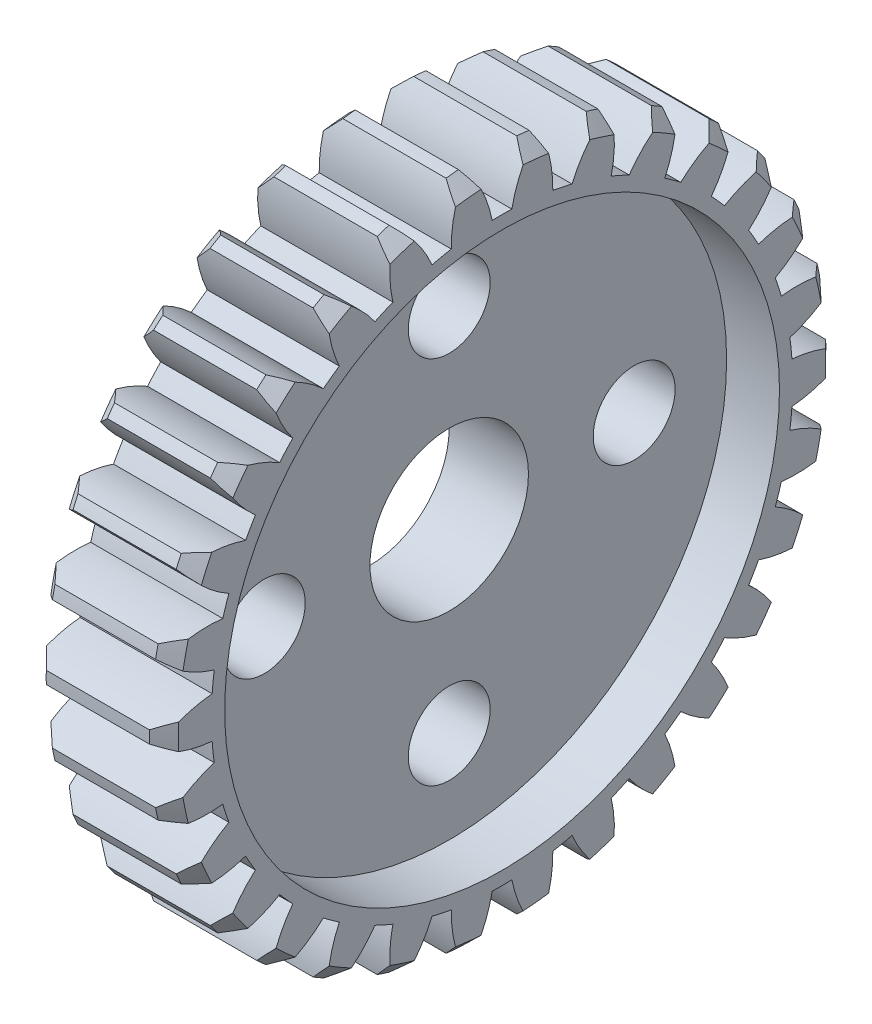
SolidWorks part; units mm, degrees
ref_plane "Plane1" through (0, 0, 0) normal (0, 0, 1) x (1, 0, 0)
ref_plane "Plane2" through (0, 0, 0) normal (0, 1, 0) x (1, 0, 0)
ref_plane "Plane3" through (0, 0, 0) normal (1, 0, 0) x (0, 0, -1)
sketch "HoldingSke" plane through (0, 0, 0) normal (0, 1, 0) x (1, 0, 0)
  line L0 (0, 0) -> (1.0825, -0.625)
  line L1 (-15, 0) -> (100, 0) construction
  line L2 (0, 0) -> (-2.1039, 2.3779)
  line L3 (0, 0) -> (-11.863, 4.5341)
  line L4 (0, 0) -> (7.479, 4.318)
  line L5 (0, 0) -> (-46.8476, -17.4728)
  line L6 (0, 0) -> (-4.1448, -2.7965)
  line L7 (-2.1039, 2.3779) -> (8.6586, 51.2059)
  line L8 (-76.2, 54.61) -> (-75.2, 54.61)
  line L9 (-71.009, 38.7566) -> (-53.1078, 45.2721)
  line L10 (-76.2, 71.12) -> (104.1128, 71.12)
  line L11 (0, 0) -> (-5, 0)
  line L12 (-76.2, 101.6) -> (-76.17, 101.6)
  line L13 (24.9733, 27.94) -> (52.9518, 28.4284)
  line L14 (24.9733, 27.94) -> (24.9743, 27.94)
  line L15 (24.9733, 27.94) -> (100.4006, 29.5858)
  line L16 (-63.627, -0.8) -> (-12.827, -0.8)
  circle A0 centre (0, 0) radius 3
  circle A1 centre (0, 0) radius 10.999
  circle A2 centre (0, 0) radius 37.5
  circle A3 centre (0, 0) radius 3
  dimension "MHD" = 21.998
  dimension "Hub_dia" = 75
  dimension "Bore" = 6
  dimension "MBD" = 6
  dimension "Num_teeth" = 30
  dimension "Pitch" = 1.25
  dimension "Overall_len" = 50
  dimension "Show_teeth" = 30
  dimension "Thickness" = 5
  dimension "OAL" = 50.0001
  dimension "T_dim" = 1
  dimension "Ap" = 20
  dimension "H" = 19.05
  dimension "Pitch_radius" = 180.3128
  dimension "Width" = 5
  dimension "Backlash" = 0.03
  dimension "Addendum_fac" = 1
  dimension "Dedendum_fac" = 1.25
  dimension "Clearance_fac" = 0.25
  dimension "Dedendum_add" = 0.001
  dimension "Module" = 0.8
sketch "BasProSke" plane through (0, 0, 0) normal (0, 1, 0) x (1, 0, 0)
  line L0 (-10, 0) -> (60, 0) construction
  line L1 (0, 0) -> (0, 12.8)
  line L2 (0, 0) -> (5, 0)
  line L3 (5, 0) -> (5, 12.8)
  line L4 (5, 12.8) -> (0, 12.8)
  dimension "Thickness" = 5
  dimension "Diameter" = 25.6
revolve "Base-Revolve" add sketch "BasProSke" angle 360 about L0
sketch "TooCutSke" plane through (0, 0, 0) normal (1, 0, 0) x (0, 0, -1)
  line L1 (0, 0) -> (0, 107) construction
  line L2 (0, 0) -> (-0.6805, 11.9807) construction
  line L3 (0, 0) -> (-2.5058, 23.8411) construction
  line L4 (-0.6805, 11.9807) -> (-1.2529, 11.9205) construction
  arc A0 (0.3724, 10.9927) -> (-0.3724, 10.9927) centre (0, 0) ccw
  arc A1 (1.1205, 12.7764) -> (-1.1205, 12.7764) centre (0, 0) ccw
  circle A2 centre (0, 0) radius 12 construction
  circle A3 centre (0, 0) radius 11.2763 construction
  arc A4 (-0.3724, 10.9927) -> (-1.1205, 12.7764) centre (-5.0822, 10.0661) ccw
  arc A5 (1.1205, 12.7764) -> (0.3724, 10.9927) centre (5.0822, 10.0661) ccw
  dimension "Root_dia" = 21.998
  dimension "Overcut_dia" = 25.6508
  dimension "Pitch_dia" = 24
  dimension "Base_dia" = 22.5526
  dimension "Flank_rad" = 4.8
  dimension "Half_ang" = 6
  dimension "Half_CT" = 0.5755
extrude "ToothCut" cut sketch "TooCutSke" along normal through all
fillet "Breaks" [suppressed] radius 0.016
fillet "RootFillets" [suppressed] radius 0.201
pattern_circular "TeethCuts" count 30 every 12 about axis through (-10, 0, 0) along (1, 0, 0) of "ToothCut", "RootFillets", "Breaks"
sketch "HubNeaOneSke" plane through (0, 0, 0) normal (-1, 0, 0) x (0, 0, 1)
  circle A0 centre (0, 0) radius 10.999
  dimension "Diameter" = 21.998
extrude "HubNearOne" [suppressed] add sketch "HubNeaOneSke" along normal blind 45.0001
sketch "HubNeaBotSke" plane through (0, 0, 0) normal (-1, 0, 0) x (0, 0, 1)
  circle A0 centre (0, 0) radius 10.999
  dimension "Diameter" = 21.998
extrude "HubNearBoth" [suppressed] add sketch "HubNeaBotSke" along normal blind 22.5
ref_plane "FarPln" through (5, 0, 0) normal (1, 0, 0) x (0, 0, -1)
sketch "HubFarSke" plane through (5, 0, 0) normal (1, 0, 0) x (0, 0, -1)
  circle A0 centre (0, 0) radius 10.999
  dimension "Diameter" = 21.998
extrude "HubFar" [suppressed] add sketch "HubFarSke" along normal blind 22.5
sketch "BorSke" plane through (0, 0, 0) normal (1, 0, 0) x (0, 0, -1)
  circle A0 centre (0, 0) radius 3
  dimension "Diameter" = 6
extrude "Bore" cut sketch "BorSke" along normal mid plane 100.0001
sketch "KeySke" plane through (0, 0, 0) normal (1, 0, 0) x (0, 0, -1)
  line L0 (-1, 0) -> (-1, 4)
  line L1 (-1, 4) -> (1, 4)
  line L2 (1, 4) -> (1, 0)
  line L3 (0, 0) -> (0, 34) construction
  line L4 (-1, 0) -> (1, 0)
  dimension "Offset" = 4
  dimension "Width" = 2
extrude "Keyway" [suppressed] cut sketch "KeySke" along normal mid plane 100.0001
pattern_circular "Keyway2" [suppressed] count 2 every 90 about axis through (-10, 0, 0) along (1, 0, 0)
sketch "草图1" plane through (5, 0, 0) normal (1, 0, 0) x (0, 0, -1)
  circle A0 centre (0, 0) radius 10.5
  dimension "D1" = 21
extrude "切除-拉伸1" cut sketch "草图1" against normal blind 2
sketch "草图2" plane through (3, 0, 0) normal (1, 0, 0) x (0, 0, -1)
  circle A0 centre (0, 0) radius 7 construction
  circle A1 centre (0, 7) radius 1.55
  circle A2 centre (7, 0) radius 1.55
  circle A3 centre (0, -7) radius 1.55
  circle A4 centre (-7, 0) radius 1.55
  point P14 (0, 0)
  dimension "D1" = 3.1
  dimension "D3" = 14
  dimension "D2" = 4
extrude "切除-拉伸2" cut sketch "草图2" against normal blind 5
sketch "草图3" plane through (0, 0, 0) normal (0, 0, 1) x (1, 0, 0)
  line L0 (0, 15.3483) -> (0, 12.2523)
  line L1 (0, 12.2523) -> (3.096, 15.3483)
  line L9 (3.096, 15.3483) -> (0, 15.3483)
  line L10 (0, 12.7032) -> (0, 10.8299) construction
  line L11 (0, 12.7523) -> (5, 12.7523) construction
  dimension "D1" = 45
  dimension "D2" = 0.5
sketch "草图4" plane through (0, 0, 0) normal (-1, 0, 0) x (0, 0, 1)
  circle A0 centre (0, 0) radius 12.2523
sweep "切除-扫描1" cut profiles "草图3" path "草图4"
ref_plane "基准面1" through (2.5, 0, 0) normal (-1, 0, 0) x (0, 0, 1)
mirror "镜向1" about plane through (2.5, 0, 0) normal (-1, 0, 0) of "切除-扫描1"
equation "' \"Module@HoldingSke\" = 6.35"
equation "' \"Num_teeth@HoldingSke\" = 12"
equation "' \"Ap@HoldingSke\" =  20"
equation "' \"Ap@HoldingSke\" = 20"
equation "' \"Width@HoldingSke\" = 0.5 * 25.4"
equation "' \"Hub_dia@HoldingSke\"= 1 * 25.4"
equation "' \"Hub_dia@HoldingSke\" = 1 * 25.4"
equation "' \"Overall_len@HoldingSke\" = 1.0 * 25.4"
equation "' \"Bore@HoldingSke\" = 0.75 * 25.4"
equation "' \"T_dim@HoldingSke\" = 0.1 * 25.4"
equation "' \"Width@KeySke\" = 0.25 * 25.4"
equation "' \"Show_teeth@HoldingSke\" = 13"
equation "' \"Backlash@HoldingSke\" = 0.009 * 25.4"
equation "' \"Addendum_fac@HoldingSke\" = 1.0"
equation "' \"Dedendum_fac@HoldingSke\" = 1.25"
equation "' \"Dedendum_add@HoldingSke\" = 0.00005 * 25.4"
equation "' \"Clearance_fac@HoldingSke\" = 0.25"
equation "\"Pitch@HoldingSke\" = 1 / \"Module@HoldingSke\""
equation "\"Overcut_dia@TooCutSke\" = (\"Num_teeth@HoldingSke\" + 2 * \"Addendum_fac@HoldingSke\") / \"Pitch@HoldingSke\" + 0.002 * 25.4"
equation "\"Pitch_dia@TooCutSke\" = \"Num_teeth@HoldingSke\" / \"Pitch@HoldingSke\""
equation "\"Base_dia@TooCutSke\" = \"Num_teeth@HoldingSke\" / \"Pitch@HoldingSke\" * cos((\"Ap@HoldingSke\"  * 3.14159265 / 180))"
equation "\"Root_dia@TooCutSke\" = (\"Num_teeth@HoldingSke\" + 2) / \"Pitch@HoldingSke\" - 2 * (\"Addendum_fac@HoldingSke\" + \"Dedendum_fac@HoldingSke\") / \"Pitch@HoldingSke\" - \"Dedendum_add@HoldingSke\" * 2"
equation "\"Half_ang@TooCutSke\" = 180 / \"Num_teeth@HoldingSke\""
equation "\"Half_CT@TooCutSke\" = \"Num_teeth@HoldingSke\" / \"Pitch@HoldingSke\" * sin((3.14159265 / 2 / \"Num_teeth@HoldingSke\")) / 2 - 7 * \"Backlash@HoldingSke\" / 4"
equation "\"Flank_rad@TooCutSke\" = \"Num_teeth@HoldingSke\" / \"Pitch@HoldingSke\" / 5"
equation "\"Radius@RootFillets\" = \"Clearance_fac@HoldingSke\" / \"Pitch@HoldingSke\" + \"Dedendum_add@HoldingSke\""
equation "\"Break_rad@Breaks\" = 0.02 / \"Pitch@HoldingSke\""
equation "\"Thickness@HoldingSke\" = \"Width@HoldingSke\""
equation "\"OAL@HoldingSke\" = \"Thickness@HoldingSke\""
equation "\"MHD@HoldingSke\" = (\"Num_teeth@HoldingSke\" + 2) / \"Pitch@HoldingSke\" - 2 * (\"Addendum_fac@HoldingSke\" + \"Dedendum_fac@HoldingSke\")  / \"Pitch@HoldingSke\" - \"Dedendum_add@HoldingSke\" * 2"
equation "\"MBD@HoldingSke\" = (\"Num_teeth@HoldingSke\" + 2) / \"Pitch@HoldingSke\" - 2 * (\"Addendum_fac@HoldingSke\" + \"Dedendum_fac@HoldingSke\")  / \"Pitch@HoldingSke\" - \"Dedendum_add@HoldingSke\" * 2 - 0.002 * 25.4"
equation "\"MHD@HoldingSke\" = ((sgn( \"MHD@HoldingSke\" - \"Hub_dia@HoldingSke\" )-1)*( \"MHD@HoldingSke\" - \"Hub_dia@HoldingSke\" ))/-2+ \"Hub_dia@HoldingSke\""
equation "\"MBD@HoldingSke\" = ((sgn( \"MBD@HoldingSke\" - \"Bore@HoldingSke\" )-1)*( \"MBD@HoldingSke\" - \"Bore@HoldingSke\" ))/-2+ \"Bore@HoldingSke\""
equation "\"OAL@HoldingSke\" = ((sgn( \"OAL@HoldingSke\" - \"Overall_len@HoldingSke\" )+1)*( \"OAL@HoldingSke\" - \"Overall_len@HoldingSke\" ))/2 + \"Overall_len@HoldingSke\" + 0.000002 * 25.4"
equation "\"Num_teeth@TeethCuts\" = int( \"Show_teeth@HoldingSke\" ) + 1"
equation "\"Num_teeth@TeethCuts\" = ((sgn( \"Num_teeth@TeethCuts\" - \"Num_teeth@HoldingSke\" )-1)*( \"Num_teeth@TeethCuts\" - \"Num_teeth@HoldingSke\" ))/-2+ \"Num_teeth@HoldingSke\""
equation "\"Num_teeth@TeethCuts\" = ((sgn( \"Num_teeth@TeethCuts\" - 2.0)+1)*( \"Num_teeth@TeethCuts\" - 2.0))/2 +2.0"
equation "\"Angle@TeethCuts\" = 360.0 / \"Num_teeth@HoldingSke\""
equation "\"Diameter@BasProSke\" = (\"Num_teeth@HoldingSke\" + 2 * \"Addendum_fac@HoldingSke\") / \"Pitch@HoldingSke\""
equation "\"Thickness@BasProSke\"  = \"Thickness@HoldingSke\""
equation "' \"Fillet_rad@BasProSke\" =  \"Thickness@HoldingSke\" * 0.05"
equation "' \"Fillet_rad@BasProSke\" = \"Thickness@HoldingSke\" * 0.05"
equation "\"MHD@HoldingSke\" = ((sgn( \"MHD@HoldingSke\" - \"Root_dia@TooCutSke\" )-1)*( \"MHD@HoldingSke\" - \"Root_dia@TooCutSke\" ))/-2+ \"Root_dia@TooCutSke\""
equation "\"Diameter@HubNeaOneSke\" = \"MHD@HoldingSke\""
equation "\"Length@HubNearOne\" = \"OAL@HoldingSke\" - \"Thickness@BasProSke\""
equation "\"Diameter@HubNeaBotSke\" = \"MHD@HoldingSke\""
equation "\"Length@HubNearBoth\" = ( \"OAL@HoldingSke\" - \"Thickness@BasProSke\" ) / 2.0"
equation "\"Thickness@FarPln\" = \"Thickness@BasProSke\""
equation "\"Diameter@HubFarSke\" = \"MHD@HoldingSke\""
equation "\"Length@HubFar\" = ( \"OAL@HoldingSke\" - \"Thickness@BasProSke\" ) / 2.0"
equation "\"Diameter@BorSke\" = \"MBD@HoldingSke\""
equation "\"D1@Bore\" = \"OAL@HoldingSke\" * 2.0"
equation "\"D1@Keyway\" = \"OAL@HoldingSke\" * 2.0"
equation "\"Offset@KeySke\" = \"T_dim@HoldingSke\" + \"MBD@HoldingSke\" / 2.0"
